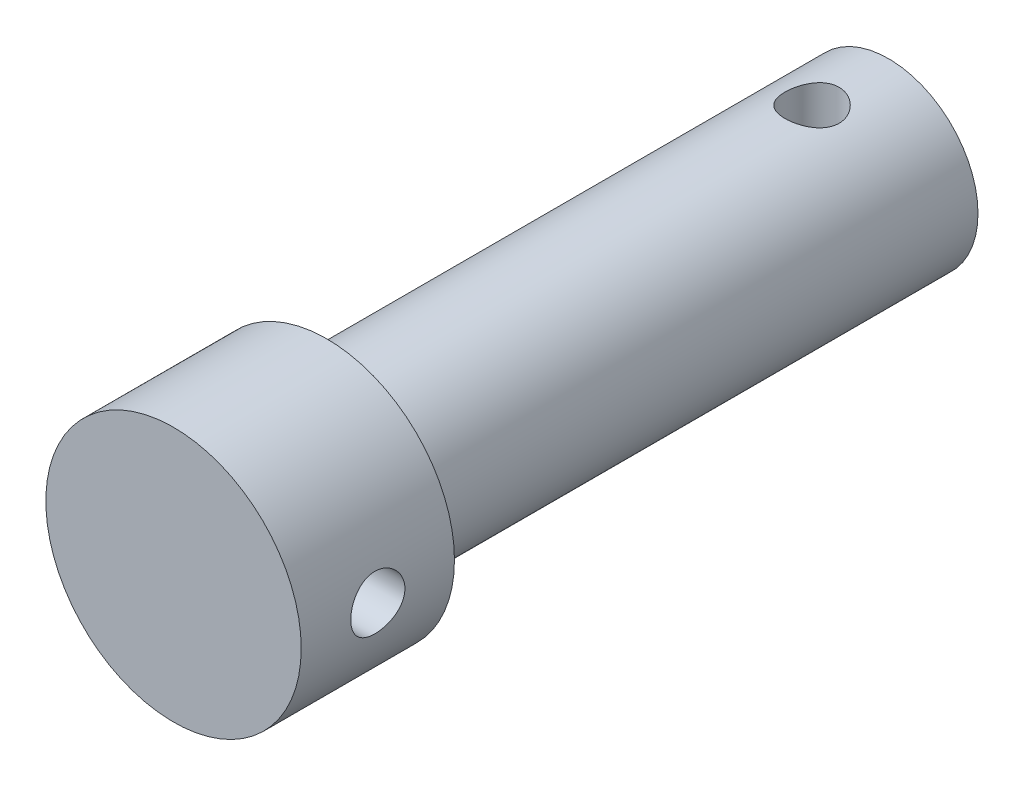
SolidWorks part; units mm, degrees
ref_plane "Front" through (0, 0, 0) normal (0, 0, 1) x (1, 0, 0)
ref_plane "Top" through (0, 0, 0) normal (0, 1, 0) x (1, 0, 0)
ref_plane "Right" through (0, 0, 0) normal (1, 0, 0) x (0, 0, -1)
sketch "Sketch1" plane through (0, 0, 0) normal (0, 0, 1) x (1, 0, 0)
  circle A0 centre (0, 0) radius 11.1125
  circle A1 centre (0, 0) radius 5.08
  dimension "D1" = 22.225
  dimension "D2" = 10.16
extrude "Boss-Extrude1" add sketch "Sketch1" along normal blind 88.9
sketch "Sketch4" plane through (0, 0, 88.9) normal (0, 0, 1) x (1, 0, 0)
  circle A0 centre (0, 0) radius 15.875
extrude "Boss-Extrude2" add sketch "Sketch4" against normal blind 19.05
sketch "Sketch5" plane through (0, 0, 0) normal (1, 0, 0) x (0, 0, -1)
  line L1 (-88.9, 15.875) -> (-88.9, -15.875) construction
  line L2 (-69.85, 15.875) -> (-88.9, 15.875) construction
  circle A0 centre (-79.375, 0) radius 3.3655
  point P2 (0, 0)
  point P3 (-80.2393, 3.2063)
  point P4 (0, 0)
  point P5 (0, 0)
  point P6 (-86.5535, 1.8469)
  point P7 (0, 0)
  dimension "D1" = 6.731
  dimension "D2" = 9.525
  dimension "D3" = 15.875
extrude "Cut-Extrude1" cut sketch "Sketch5" against normal through all both and the other way through all
sketch "Sketch7" plane through (0, 0, 0) normal (0, 1, 0) x (1, 0, 0)
  line L1 (5.08, 0) -> (-5.08, 0) construction
  line L3 (11.1125, 0) -> (-11.1125, 0) construction
  circle A0 centre (0, -9.525) radius 3.3655
  point P6 (0, -9.525)
  dimension "D1" = 9.525
  dimension "D2" = 9.525
  dimension "D3" = 9.525
  dimension "D4" = 9.525
extrude "Cut-Extrude2" cut sketch "Sketch7" against normal through all both and the other way through all
